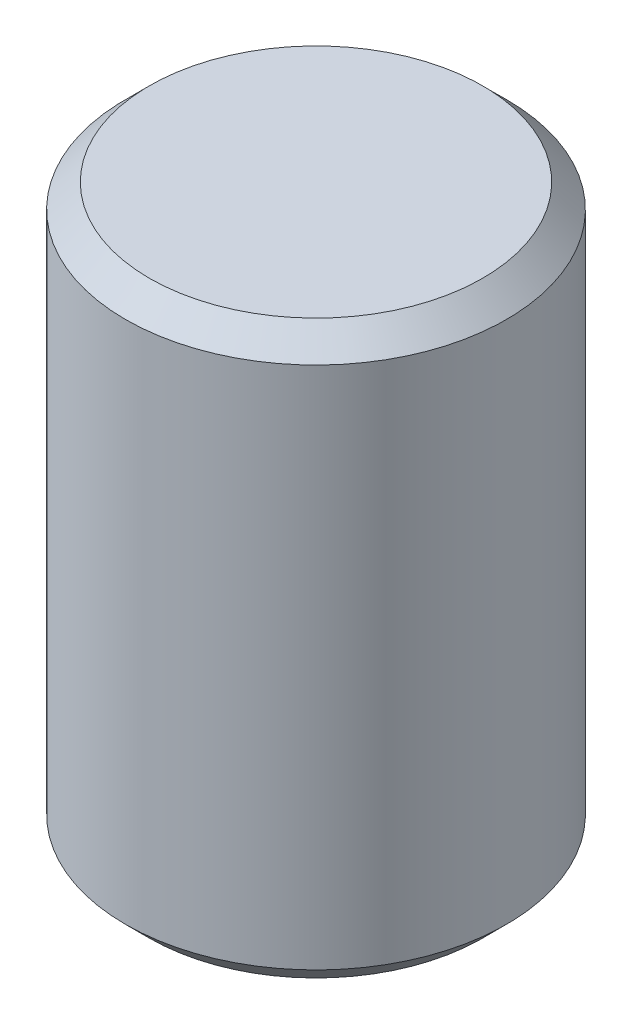
SolidWorks part; units mm, degrees
ref_plane "Front Plane" through (0, 0, 0) normal (0, 0, 1) x (1, 0, 0)
ref_plane "Top Plane" through (0, 0, 0) normal (0, 1, 0) x (1, 0, 0)
ref_plane "Right Plane" through (0, 0, 0) normal (1, 0, 0) x (0, 0, -1)
sketch "Sketch1" plane through (0, 0, 0) normal (0, 1, 0) x (1, 0, 0)
  circle A0 centre (0, 0) radius 4
  dimension "D1" = 8
extrude "Boss-Extrude1" add sketch "Sketch1" along normal mid plane 12
chamfer "Chamfer1" distance 0.5 angle 45 2 edges at (0, -6, 4) (0, 6, 4)
